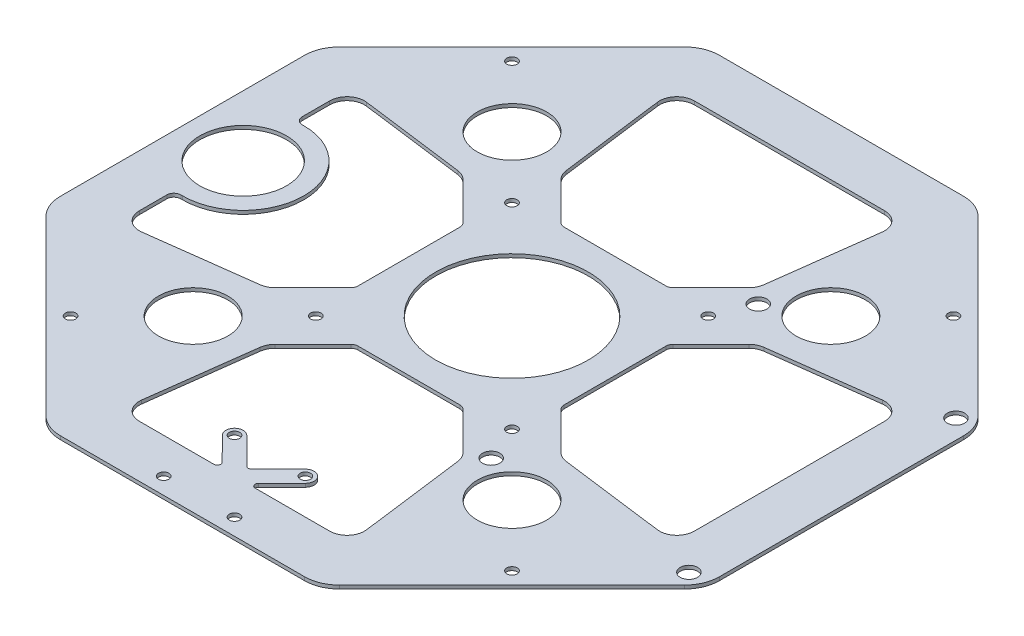
SolidWorks part; units mm, degrees
material "Hexcel AS4C (3000 Filaments)"
ref_plane "Front Plane" through (0, 0, 0) normal (0, 0, 1) x (1, 0, 0)
ref_plane "Top Plane" through (0, 0, 0) normal (0, 1, 0) x (1, 0, 0)
ref_plane "Right Plane" through (0, 0, 0) normal (1, 0, 0) x (0, 0, -1)
sketch "Sketch1" plane through (0, 0, 0) normal (0, 1, 0) x (1, 0, 0)
  line L22 (27.0793, 41.2214) -> (16.1421, 30.2843)
  line L24 (30.2843, 16.1421) -> (41.2214, 27.0793)
  line L26 (41.2214, -27.0793) -> (30.2843, -16.1421)
  line L27 (16.1421, -30.2843) -> (27.0793, -41.2214)
  line L30 (-27.0793, -41.2214) -> (-16.1421, -30.2843)
  line L31 (-30.2843, -16.1421) -> (-41.2214, -27.0793)
  line L34 (-41.2214, 27.0793) -> (-30.2843, 16.1421)
  line L35 (-16.1421, 30.2843) -> (-27.0793, 41.2214)
  line L36 (32.4086, 74.3595) -> (28.5026, 44.1165)
  line L38 (-14.7279, 29.6985) -> (14.7279, 29.6985)
  line L39 (29.6985, 14.7279) -> (29.6985, -14.7279)
  line L40 (14.7279, -29.6985) -> (-14.7279, -29.6985)
  line L41 (-29.6985, -14.7279) -> (-29.6985, 14.7279)
  line L42 (92.0711, 42.2792) -> (42.2792, 92.0711)
  line L52 (27.4498, 80) -> (-27.4498, 80)
  line L58 (80, -27.4498) -> (80, 27.4498)
  line L59 (44.1165, 28.5026) -> (74.3595, 32.4086)
  line L60 (74.3595, -32.4086) -> (44.1165, -28.5026)
  line L61 (28.5026, -44.1165) -> (32.4086, -74.3595)
  line L62 (-32.4086, -74.3595) -> (-28.5026, -44.1165)
  line L63 (-44.1165, -28.5026) -> (-74.3595, -32.4086)
  line L64 (-74.3595, 32.4086) -> (-44.1165, 28.5026)
  line L65 (-28.5026, 44.1165) -> (-32.4086, 74.3595)
  line L66 (80, 33.1371) -> (33.1371, 80) [skipped]
  line L67 (33.1371, -80) -> (80, -33.1371) [skipped]
  line L68 (-80, -33.1371) -> (-33.1371, -80) [skipped]
  line L69 (-33.1371, 80) -> (-80, 33.1371) [skipped]
  line L70 (42.4264, 28.2843) -> (28.2843, 42.4264) [skipped]
  line L71 (35.2082, 95) -> (-35.2082, 95)
  line L72 (-92.0711, 42.2792) -> (-42.2792, 92.0711)
  line L73 (-95, 35.2082) -> (-95, -35.2082)
  line L74 (15.5563, 26.8701) -> (26.8701, 15.5563) [skipped]
  line L75 (-92.0711, -42.2792) -> (-42.2792, -92.0711)
  line L76 (-35.2082, -95) -> (35.2082, -95)
  line L77 (42.2792, -92.0711) -> (92.0711, -42.2792)
  line L78 (95, -35.2082) -> (95, 35.2082)
  line L79 (-77.5, 17.5) -> (-78, 17.5)
  line L81 (-77.5, -17.5) -> (-78, -17.5)
  line L83 (-80, 27.4498) -> (-80, -27.4498) [skipped]
  line L84 (-80, -27.4498) -> (-80, -19.5)
  line L86 (-80, 19.5) -> (-80, 27.4498)
  line L92 (6.8752, -76.6614) -> (11.9818, -71.5537)
  line L95 (3.3397, -73.1259) -> (8.4459, -68.0186)
  line L97 (6.8752, -76.6614) -> (5.244, -78.293)
  line L98 (3.3397, -73.1259) -> (0.7072, -75.759)
  line L99 (-27.4498, -80) -> (-5.9512, -80)
  line L100 (-6.8752, -76.6614) -> (-5.244, -78.293)
  line L101 (-6.8752, -76.6614) -> (-11.9818, -71.5537)
  line L102 (-3.3397, -73.1259) -> (-0.7072, -75.759)
  line L103 (-3.3397, -73.1259) -> (-8.4459, -68.0186)
  line L104 (-27.4498, -80) -> (27.4498, -80) [skipped]
  line L105 (5.9512, -80) -> (27.4498, -80)
  arc A0 (-27.0793, -41.2214) -> (-28.5026, -44.1165) centre (-23.5437, -44.7569) ccw
  circle A1 centre (63.6396, 63.6396) radius 1.5
  circle A2 centre (28.2843, 28.2843) radius 1.5
  circle A3 centre (63.6396, -63.6396) radius 1.5
  circle A4 centre (28.2843, -28.2843) radius 1.5
  circle A5 centre (-63.6396, -63.6396) radius 1.5
  circle A6 centre (-28.2843, -28.2843) radius 1.5
  circle A7 centre (-63.6396, 63.6396) radius 1.5
  circle A8 centre (-28.2843, 28.2843) radius 1.5
  arc A9 (-32.4086, -74.3595) -> (-27.4498, -80) centre (-27.4498, -75) ccw
  arc A10 (27.4498, -80) -> (32.4086, -74.3595) centre (27.4498, -75) ccw
  arc A11 (28.5026, -44.1165) -> (27.0793, -41.2214) centre (23.5437, -44.7569) ccw
  arc A12 (41.2214, -27.0793) -> (44.1165, -28.5026) centre (44.7569, -23.5437) ccw
  arc A13 (74.3595, -32.4086) -> (80, -27.4498) centre (75, -27.4498) ccw
  arc A14 (80, 27.4498) -> (74.3595, 32.4086) centre (75, 27.4498) ccw
  arc A15 (44.1165, 28.5026) -> (41.2214, 27.0793) centre (44.7569, 23.5437) ccw
  arc A16 (27.0793, 41.2214) -> (28.5026, 44.1165) centre (23.5437, 44.7569) ccw
  arc A17 (-28.5026, 44.1165) -> (-27.0793, 41.2214) centre (-23.5437, 44.7569) ccw
  arc A18 (32.4086, 74.3595) -> (27.4498, 80) centre (27.4498, 75) ccw
  arc A19 (-27.4498, 80) -> (-32.4086, 74.3595) centre (-27.4498, 75) ccw
  arc A20 (-41.2214, 27.0793) -> (-44.1165, 28.5026) centre (-44.7569, 23.5437) ccw
  arc A21 (-41.2214, -27.0793) -> (-44.1165, -28.5026) centre (-44.7569, -23.5437) cw
  arc A22 (-74.3595, -32.4086) -> (-80, -27.4498) centre (-75, -27.4498) cw
  arc A23 (-80, 27.4498) -> (-74.3595, 32.4086) centre (-75, 27.4498) cw
  circle A33 centre (45.9619, 45.9619) radius 10
  circle A34 centre (45.9619, -45.9619) radius 10
  circle A35 centre (-45.9619, -45.9619) radius 10
  circle A36 centre (0, 0) radius 22
  arc A37 (-16.1421, 30.2843) -> (-14.7279, 29.6985) centre (-14.7279, 31.6985) ccw
  arc A38 (14.7279, 29.6985) -> (16.1421, 30.2843) centre (14.7279, 31.6985) ccw
  arc A39 (29.6985, 14.7279) -> (30.2843, 16.1421) centre (31.6985, 14.7279) cw
  arc A40 (29.6985, -14.7279) -> (30.2843, -16.1421) centre (31.6985, -14.7279) ccw
  arc A41 (16.1421, -30.2843) -> (14.7279, -29.6985) centre (14.7279, -31.6985) ccw
  arc A42 (-14.7279, -29.6985) -> (-16.1421, -30.2843) centre (-14.7279, -31.6985) ccw
  arc A43 (-30.2843, -16.1421) -> (-29.6985, -14.7279) centre (-31.6985, -14.7279) ccw
  arc A44 (-29.6985, 14.7279) -> (-30.2843, 16.1421) centre (-31.6985, 14.7279) ccw
  arc A53 (-95, -35.2082) -> (-92.0711, -42.2792) centre (-85, -35.2082) ccw
  arc A54 (-42.2792, -92.0711) -> (-35.2082, -95) centre (-35.2082, -85) ccw
  arc A55 (35.2082, -95) -> (42.2792, -92.0711) centre (35.2082, -85) ccw
  arc A56 (92.0711, -42.2792) -> (95, -35.2082) centre (85, -35.2082) ccw
  arc A57 (95, 35.2082) -> (92.0711, 42.2792) centre (85, 35.2082) ccw
  arc A58 (42.2792, 92.0711) -> (35.2082, 95) centre (35.2082, 85) ccw
  arc A59 (-35.2082, 95) -> (-42.2792, 92.0711) centre (-35.2082, 85) ccw
  arc A60 (-92.0711, 42.2792) -> (-95, 35.2082) centre (-85, 35.2082) ccw
  circle A61 centre (32.5, 38.5) radius 2.5
  circle A62 centre (89.5, 38.5) radius 2.5
  circle A63 centre (32.5, -38.5) radius 2.5
  circle A64 centre (89.5, -38.5) radius 2.5
  circle A83 centre (-77.5, 0) radius 12.5
  arc A84 (-77.5, 17.5) -> (-77.5, -17.5) centre (-77.5, 0) cw
  circle A85 centre (-45.9619, 45.9619) radius 10
  circle A87 centre (-10.2138, -90.2138) radius 1.5
  circle A89 centre (10.2138, -69.7862) radius 1.5
  circle A90 centre (10.2138, -90.2138) radius 1.5
  arc A93 (11.9818, -71.5537) -> (8.4459, -68.0186) centre (10.2138, -69.7862) ccw
  circle A94 centre (-10.2138, -69.7862) radius 1.5 [skipped]
  circle A95 centre (-10.2138, -69.7862) radius 1.5
  arc A96 (-11.9818, -71.5537) -> (-8.4459, -68.0186) centre (-10.2138, -69.7862) cw
  arc A97 (0.7072, -75.759) -> (-0.7072, -75.759) centre (0, -75.0519) cw
  arc A98 (5.9512, -80) -> (5.244, -78.293) centre (5.9512, -79) cw
  arc A99 (-5.9512, -80) -> (-5.244, -78.293) centre (-5.9512, -79) ccw
  arc A100 (-80, 19.5) -> (-78, 17.5) centre (-78, 19.5) ccw
  arc A101 (-80, -19.5) -> (-78, -17.5) centre (-78, -19.5) cw
  point P28 (0, 0)
  point P46 (0, 0)
  point P71 (0, 0)
  point P123 (0, 0)
  point P171 (0, -80)
  dimension "D2" = 4
  dimension "D1" = 4
  dimension "D3" = 5
  dimension "D4" = 2
  dimension "D5" = 10
  dimension "D6" = 4
  dimension "D7" = 1
  dimension "D8" = 1
  dimension "D9" = 2
  dimension "D10" = 4
extrude "Boss-Extrude1" add sketch "Sketch1" along normal blind 1
